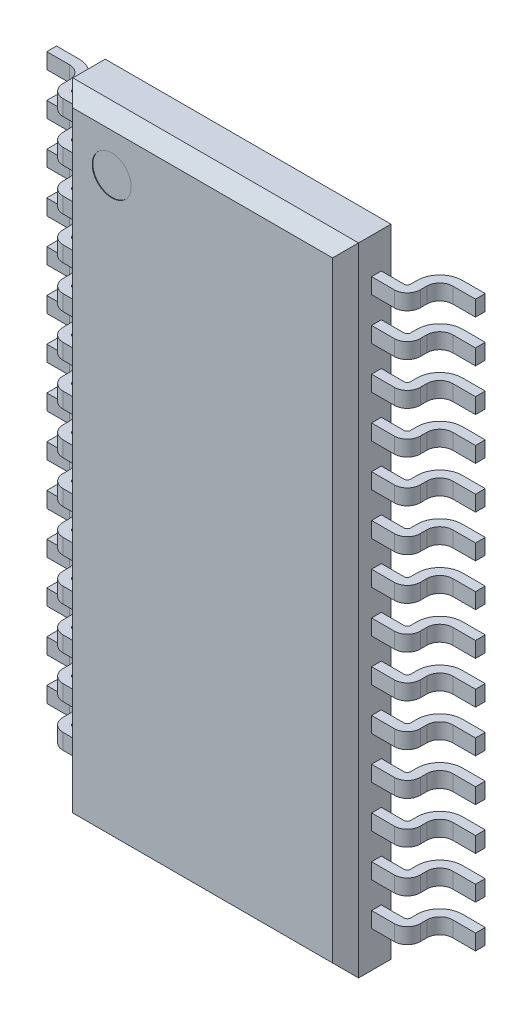
SolidWorks part; units mm, degrees
ref_plane "前视基准面" through (0, 0, 0) normal (0, 0, 1) x (1, 0, 0)
ref_plane "上视基准面" through (0, 0, 0) normal (0, 1, 0) x (1, 0, 0)
ref_plane "右视基准面" through (0, 0, 0) normal (1, 0, 0) x (0, 0, -1)
ref_plane "基准面1" through (0, 0, 0.15) normal (0, 0, 1) x (1, 0, 0)
sketch "草图1" plane through (0, 0, 0.15) normal (0, 0, 1) x (1, 0, 0)
  line L1 (-2.2, 4.9) -> (2.2, 4.9)
  line L2 (-2.2, 4.9) -> (-2.2, -4.9)
  line L3 (-2.2, -4.9) -> (2.2, -4.9)
  line L4 (2.2, 4.9) -> (2.2, -4.9)
  dimension "D1" = 4.4
  dimension "D2" = 9.8
  dimension "D3" = 4.9
  dimension "D4" = 2.2
extrude "拉伸1" add sketch "草图1" along normal blind 0.9
chamfer "倒角1" distance 0.2 angle 45 8 edges at (2.2, 0, 1.05) (0, 4.9, 1.05) (-2.2, 0, 1.05) (0, 4.9, 0.15) (2.2, 0, 0.15) (0, -4.9, 0.15) (-2.2, 0, 0.15) (0, -4.9, 1.05)
ref_plane "基准面2" through (0, 0.33, 0) normal (0, 1, 0) x (-1, 0, 0)
sketch "草图5" plane through (0, 0.33, 0) normal (0, 1, 0) x (1, 0, 0)
  line L0 (-2.2, -0.65) -> (-2.55, -0.65)
  line L1 (-2.2, -0.85) -> (-2.2, -0.35) construction
  line L2 (-2.75, -0.45) -> (-2.75, -0.35)
  line L3 (-2.95, -0.15) -> (-3.3, -0.15)
  line L5 (-2, -1.05) -> (2, -1.05) construction
  arc A0 (-2.75, -0.45) -> (-2.55, -0.65) centre (-2.55, -0.45) ccw
  arc A1 (-2.95, -0.15) -> (-2.75, -0.35) centre (-2.95, -0.35) cw
  point P13 (-2.75, -0.15)
  dimension "D5" = 0.2
  dimension "D1" = 3.3
  dimension "D2" = 0.15
  dimension "D3" = 0.4
  dimension "D4" = 0.55
sketch "草图6" plane through (-2.2, 0, 0) normal (1, 0, 0) x (0, 0, -1)
  line L2 (-0.5, 0.45) -> (-0.65, 0.45)
  line L3 (-0.5, 0.45) -> (-0.5, 0.21)
  line L4 (-0.5, 0.21) -> (-0.65, 0.21)
  line L5 (-0.65, 0.45) -> (-0.65, 0.21)
  dimension "D1" = 0.15
  dimension "D2" = 0.24
sweep "扫描1" add profiles "草图6" path "草图5"
pattern_linear "阵列(线性)1" count 8 spacing 0.65 along (0, -1, 0) count 7 spacing 0.65 along (0, 1, 0) of "扫描1"
mirror "镜向1" about plane through (0, 0, 0) normal (1, 0, 0) of "阵列(线性)1", "扫描1"
sketch "草图7" plane through (0, 0, 1.05) normal (0, 0, 1) x (1, 0, 0)
  line L0 (2.2, 4.9) -> (-2.2, 4.9) construction
  line L1 (-2.2, 4.9) -> (-2.2, -4.9) construction
  circle A0 centre (-1.4, 4.1) radius 0.3
  dimension "D1" = 0.6
  dimension "D2" = 0.8
  dimension "D3" = 0.8
extrude "切除-拉伸1" cut sketch "草图7" against normal blind 0.01
